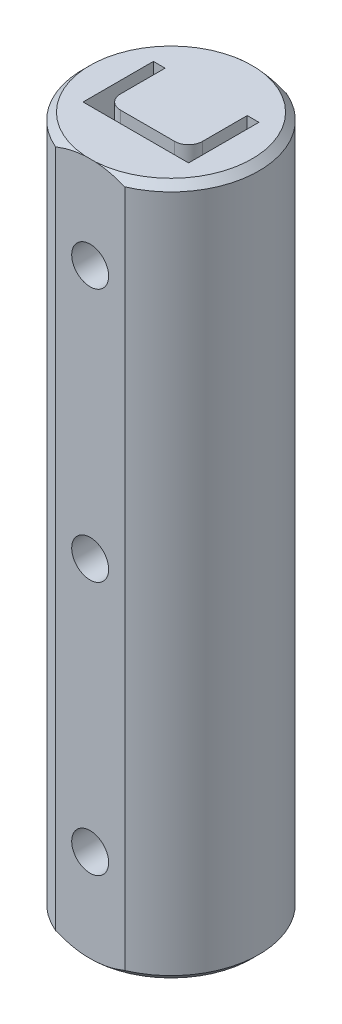
SolidWorks part; units mm, degrees
ref_plane "Front Plane" through (0, 0, 0) normal (0, 0, 1) x (1, 0, 0)
ref_plane "Top Plane" through (0, 0, 0) normal (0, 1, 0) x (1, 0, 0)
ref_plane "Right Plane" through (0, 0, 0) normal (1, 0, 0) x (0, 0, -1)
sketch "Sketch1" plane through (0, 0, 0) normal (0, 1, 0) x (1, 0, 0)
  circle A0 centre (0, 0) radius 19.05
  dimension "D1" = 38.1
extrude "Boss-Extrude1" add sketch "Sketch1" along normal blind 150
sketch "Sketch2" plane through (0, 150, 0) normal (0, 1, 0) x (1, 0, 0)
  line L0 (-11.43, -7.62) -> (11.43, -7.62)
  line L1 (-11.43, -7.62) -> (-11.43, 7.62)
  line L2 (-11.43, 7.62) -> (-8.89, 7.62)
  line L3 (-8.89, 7.62) -> (-8.89, -5.08)
  line L4 (-8.89, -5.08) -> (8.89, -5.08)
  line L5 (0, -5.08) -> (0, -7.62) construction
  line L6 (8.89, 7.62) -> (8.89, -5.08)
  line L7 (11.43, 7.62) -> (8.89, 7.62)
  line L8 (11.43, -7.62) -> (11.43, 7.62)
  line L9 (-11.43, 0) -> (0, 0) construction
  dimension "D1" = 22.86
  dimension "D2" = 15.24
  dimension "D3" = 2.54
  dimension "D4" = 2.54
extrude "Cut-Extrude1" cut sketch "Sketch2" against normal through all
fillet "Fillet1" radius 3 2 edges at (8.89, 75, 5.08) (-8.89, 75, 5.08)
sketch "Sketch3" plane through (0, 150, 0) normal (0, 1, 0) x (1, 0, 0)
  line L0 (-7.5, 17.5115) -> (7.5, 17.5115)
  line L1 (0, 0) -> (0, 17.5115) construction
  line L2 (0, 0) -> (19.05, 0) construction
  line L3 (-7.5, -17.5115) -> (7.5, -17.5115)
  circle A0 centre (0, 0) radius 19.05 construction
  arc A1 (7.5, -17.5115) -> (-7.5, -17.5115) centre (0, 0) cw
  circle A2 centre (0, 0) radius 19.05
  arc A3 (7.5, 17.5115) -> (-7.5, 17.5115) centre (0, 0) ccw
  dimension "D2" = 15
  dimension "D1" = 0
extrude "Cut-Extrude2" cut sketch "Sketch3" against normal through all
chamfer "Chamfer1" distance 1.5 angle 45 4 edges at (-19.05, 0, 0) (19.05, 0, 0) (-19.05, 150, 0) (19.05, 150, 0)
hole_wizard "Ø8.0mm Dowel Hole1" positions "Sketch4" profile "Sketch5" hole size "Ø8.0" standard "ANSI Metric" end condition through all
sketch "Sketch4" plane through (0, 0, -17.5115) normal (0, 0, -1) x (-1, 0, 0)
  line L2 (0, 0) -> (0, 20) construction
  line L3 (0, 20) -> (0, 75) construction
  line L4 (0, 75) -> (0, 130) construction
  line L5 (0, 130) -> (0, 150) construction
  line L6 (-5.89, 150) -> (5.89, 150) construction
  line L9 (0, 75) -> (19.05, 75) construction
  line L10 (19.05, 1.5) -> (19.05, 148.5) construction
  line L12 (17.55, 150) -> (1.1619, 150) construction
  point P0 (0, 130)
  point P2 (0, 75)
  point P4 (0, 20)
  point P39 (0, 0)
  point P40 (0, 0)
  dimension "D1" = 20
sketch "Sketch5" plane through (0, 130, -17.5115) normal (1, 0, 0) x (0, 1, 0)
  line L0 (0, 0) -> (0, 35.023)
  line L1 (0, 35.023) -> (4, 35.023)
  line L2 (4, 35.023) -> (4, 0)
  line L5 (4, 0) -> (0, 0)
  line L11 (0, -6.35) -> (0, 107.95) construction
  dimension "Thru Hole Dia." = 8
  dimension "Thru Hole Depth" = 35.023
sketch "Sketch6" plane through (0, 0, -17.5115) normal (0, 0, -1) x (-1, 0, 0)
  circle A0 centre (0, 130) radius 6
  circle A1 centre (0, 75) radius 6
  circle A2 centre (0, 20) radius 6
  dimension "D1" = 12
extrude "Cut-Extrude3" cut sketch "Sketch6" against normal up to surface (25.1315 mm away) up to face at (4, 130, 7.62)
